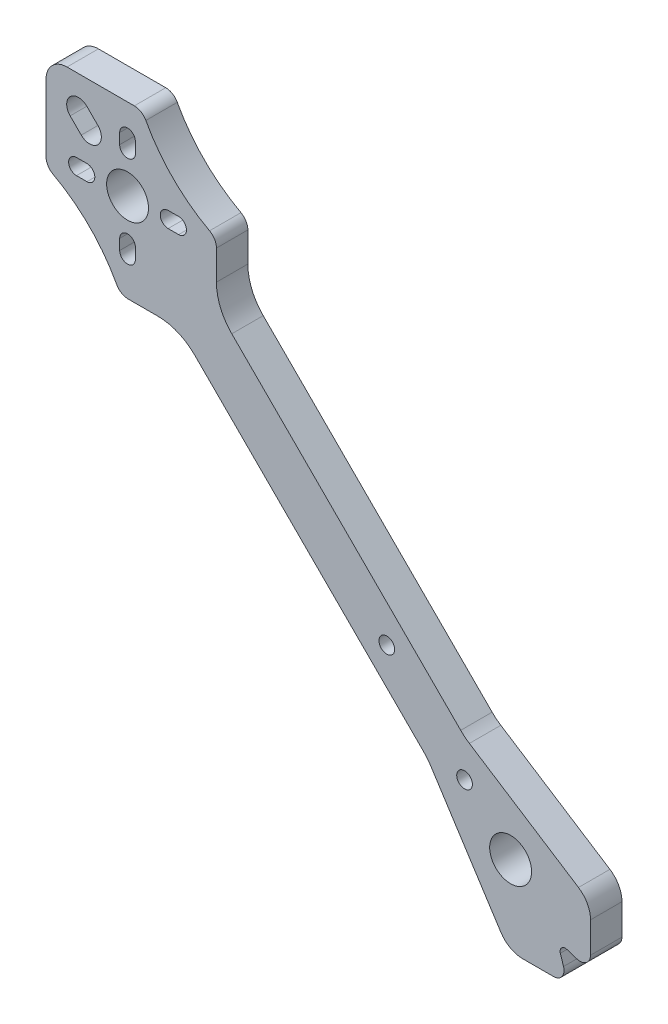
SolidWorks part; units mm, degrees
ref_plane "Alzado" through (0, 0, 0) normal (0, 0, 1) x (1, 0, 0)
ref_plane "Planta" through (0, 0, 0) normal (0, 1, 0) x (1, 0, 0)
ref_plane "Vista lateral" through (0, 0, 0) normal (1, 0, 0) x (0, 0, -1)
sketch "Croquis1" plane through (0, 0, 0) normal (0, 0, 1) x (1, 0, 0)
  line L0 (0, 0) -> (27.8544, 27.8544) construction
  line L1 (0, 0) -> (-42.4264, 42.4264) construction
  line L2 (0, 0) -> (0, 42.4264) construction
  line L3 (15.25, -15.25) -> (-15.25, -15.25) construction
  line L4 (15.25, -15.25) -> (15.25, 15.25) construction
  line L5 (15.25, 15.25) -> (-15.25, 15.25) construction
  line L6 (-15.25, -15.25) -> (-15.25, 15.25) construction
  line L7 (15.25, -15.25) -> (-15.25, 15.25) construction
  line L8 (15.25, 15.25) -> (-15.25, -15.25) construction
  line L9 (0, 42.4264) -> (-20, 42.4264) construction
  line L10 (-42.4264, 42.4264) -> (-38.8909, 45.9619) construction
  line L11 (-38.8909, 45.9619) -> (-31.0962, 38.1673) construction
  line L12 (-20, 42.7635) -> (-20, 80) construction
  line L13 (-42.4264, 42.4264) -> (-45.9619, 38.8909) construction
  line L14 (-45.9619, 38.8909) -> (-38.1673, 31.0962) construction
  line L15 (20, 42.7635) -> (20, 80) construction
  line L16 (38.8909, 45.9619) -> (31.0962, 38.1673) construction
  line L17 (42.4264, 42.4264) -> (38.8909, 45.9619) construction
  line L18 (42.4264, 42.4264) -> (45.9619, 38.8909) construction
  line L19 (-45.9619, -38.8909) -> (-38.1673, -31.0962) construction
  line L20 (0, 0) -> (-15.25, 0) construction
  line L21 (45.9619, 38.8909) -> (38.1673, 31.0962) construction
  line L22 (42.4264, -42.4264) -> (45.9619, -38.8909) construction
  line L23 (42.4264, -42.4264) -> (38.8909, -45.9619) construction
  line L24 (38.8909, -45.9619) -> (31.0962, -38.1673) construction
  line L25 (20, -42.7635) -> (20, -80) construction
  line L26 (-20, -42.7635) -> (-20, -80) construction
  line L27 (-38.8909, -45.9619) -> (-31.0962, -38.1673) construction
  line L28 (-42.4264, -42.4264) -> (-38.8909, -45.9619) construction
  line L29 (-42.4264, -42.4264) -> (-45.9619, -38.8909) construction
  line L30 (45.9619, -38.8909) -> (38.1673, -31.0962) construction
  line L31 (-20, 80) -> (20, 80) construction
  line L32 (0, 80) -> (0, 83) construction
  line L33 (-20, 80) -> (0, 83) construction
  line L34 (0, 83) -> (20, 80) construction
  line L35 (0, -80) -> (0, -83) construction
  line L36 (-20, -80) -> (20, -80) construction
  line L37 (0, -83) -> (20, -80) construction
  line L38 (-20, -80) -> (0, -83) construction
  line L39 (-11, -54) -> (-11, -67.5) construction
  line L41 (-15, -54) -> (-15, -67.5) construction
  line L43 (-13, -54) -> (-13, -67.5) construction
  line L44 (-9, -54) -> (-9, -67.5) construction
  line L45 (-7, -54) -> (-7, -67.5) construction
  line L46 (-5, -54) -> (-5, -67.5) construction
  line L47 (-3, -54) -> (-3, -67.5) construction
  line L48 (-1, -54) -> (-1, -67.5) construction
  line L49 (1, -54) -> (1, -67.5) construction
  line L50 (3, -54) -> (3, -67.5) construction
  line L51 (5, -54) -> (5, -67.5) construction
  line L52 (7, -54) -> (7, -67.5) construction
  line L53 (9, -54) -> (9, -67.5) construction
  line L54 (11, -54) -> (11, -67.5) construction
  line L55 (13, -54) -> (13, -67.5) construction
  line L56 (15, -54) -> (15, -67.5) construction
  line L57 (-11, -35) -> (-11, -48.5) construction
  line L58 (-9, -35) -> (-9, -48.5) construction
  line L59 (-7, -35) -> (-7, -48.5) construction
  line L60 (-5, -35) -> (-5, -48.5) construction
  line L61 (-3, -35) -> (-3, -48.5) construction
  line L62 (-1, -35) -> (-1, -48.5) construction
  line L63 (1, -35) -> (1, -48.5) construction
  line L64 (3, -35) -> (3, -48.5) construction
  line L65 (5, -35) -> (5, -48.5) construction
  line L66 (7, -35) -> (7, -48.5) construction
  line L67 (9, -35) -> (9, -48.5) construction
  line L68 (11, -35) -> (11, -48.5) construction
  line L69 (13, -35) -> (13, -48.5) construction
  line L70 (15, -35) -> (15, -48.5) construction
  line L71 (-15, -35) -> (-15, -48.5) construction
  line L72 (-13, -35) -> (-13, -48.5) construction
  line L73 (-15, 54) -> (-15, 67.5) construction
  line L74 (-13, 35) -> (-13, 48.5) construction
  line L75 (-15, 35) -> (-15, 48.5) construction
  line L76 (15, 35) -> (15, 48.5) construction
  line L77 (13, 35) -> (13, 48.5) construction
  line L78 (11, 35) -> (11, 48.5) construction
  line L79 (9, 35) -> (9, 48.5) construction
  line L80 (7, 35) -> (7, 48.5) construction
  line L81 (5, 35) -> (5, 48.5) construction
  line L82 (3, 35) -> (3, 48.5) construction
  line L83 (1, 35) -> (1, 48.5) construction
  line L84 (-1, 35) -> (-1, 48.5) construction
  line L85 (-3, 35) -> (-3, 48.5) construction
  line L86 (-5, 35) -> (-5, 48.5) construction
  line L87 (-7, 35) -> (-7, 48.5) construction
  line L88 (-9, 35) -> (-9, 48.5) construction
  line L89 (-11, 35) -> (-11, 48.5) construction
  line L90 (15, 54) -> (15, 67.5) construction
  line L91 (13, 54) -> (13, 67.5) construction
  line L92 (11, 54) -> (11, 67.5) construction
  line L93 (9, 54) -> (9, 67.5) construction
  line L94 (7, 54) -> (7, 67.5) construction
  line L95 (5, 54) -> (5, 67.5) construction
  line L96 (3, 54) -> (3, 67.5) construction
  line L97 (1, 54) -> (1, 67.5) construction
  line L98 (-1, 54) -> (-1, 67.5) construction
  line L99 (-3, 54) -> (-3, 67.5) construction
  line L100 (-5, 54) -> (-5, 67.5) construction
  line L101 (-7, 54) -> (-7, 67.5) construction
  line L102 (-9, 54) -> (-9, 67.5) construction
  line L103 (-13, 54) -> (-13, 67.5) construction
  line L104 (-11, 54) -> (-11, 67.5) construction
  line L105 (0, 0) -> (-8.4853, -8.4853) construction
  line L110 (-5.7118, -4.325) -> (-4.3076, -2.2188) construction
  line L111 (-4.325, -5.7118) -> (-2.2188, -4.3076) construction
  line L112 (-4.325, 5.7118) -> (-2.2188, 4.3076) construction
  line L113 (-5.7118, 4.325) -> (-4.3076, 2.2188) construction
  line L114 (5.7118, 4.325) -> (4.3076, 2.2188) construction
  line L115 (4.325, 5.7118) -> (2.2188, 4.3076) construction
  line L116 (4.325, -5.7118) -> (2.2188, -4.3076) construction
  line L117 (5.7118, -4.325) -> (4.3076, -2.2188) construction
  line L123 (-45.9619, 38.8909) -> (-31.0962, 24.0251) construction
  line L124 (-17.1122, 2.2943) -> (-30.516, 23.1236)
  line L125 (-31.8543, 24.7832) -> (-45.9619, 38.8909)
  line L126 (-45.9619, 38.8909) -> (-78.4889, 71.4178)
  line L127 (-31.0962, 24.0251) -> (-24.0251, 31.0962) construction
  line L128 (-38.8909, 45.9619) -> (-24.0251, 31.0962) construction
  line L129 (-2.2943, 17.1122) -> (-23.1236, 30.516)
  line L130 (-24.7832, 31.8543) -> (-38.8909, 45.9619)
  line L131 (-78.4889, 71.4178) -> (-71.4178, 78.4889)
  line L132 (0, 0) -> (-74.9533, 74.9533) construction
  line L135 (-74.9533, 74.9533) -> (-88.3883, 88.3883) construction
  line L168 (-38.8909, 45.9619) -> (-71.4178, 78.4889)
  line L171 (0, 0) -> (-6.364, 6.364) construction
  line L172 (-5.7629, 4.5039) -> (-5.1526, 2.6149)
  line L173 (-7.0557, 0) -> (-12.9076, 0)
  line L174 (-4.5039, 5.7629) -> (-2.6149, 5.1526)
  line L175 (0, 7.0557) -> (0, 12.9076)
  circle A0 centre (-15.25, 15.25) radius 4 construction
  circle A1 centre (-24.0416, 24.0416) radius 1.5 construction
  circle A2 centre (-38.8909, 38.8909) radius 1.5 construction
  arc A3 (-31.0962, 38.1673) -> (-20, 42.7635) centre (-26.5, 42.7635) ccw construction
  arc A4 (31.0962, 38.1673) -> (20, 42.7635) centre (26.5, 42.7635) cw construction
  circle A5 centre (38.8909, 38.8909) radius 1.5 construction
  circle A6 centre (24.0416, 24.0416) radius 1.5 construction
  circle A7 centre (15.25, 15.25) radius 4 construction
  circle A8 centre (15.25, -15.25) radius 4 construction
  circle A9 centre (24.0416, -24.0416) radius 1.5 construction
  circle A10 centre (38.8909, -38.8909) radius 1.5 construction
  arc A11 (31.0962, -38.1673) -> (20, -42.7635) centre (26.5, -42.7635) ccw construction
  circle A12 centre (-15.25, -15.25) radius 4 construction
  circle A13 centre (-24.0416, -24.0416) radius 1.5 construction
  circle A14 centre (-38.8909, -38.8909) radius 1.5 construction
  arc A15 (-31.0962, -38.1673) -> (-20, -42.7635) centre (-26.5, -42.7635) cw construction
  arc A16 (-38.1673, -31.0962) -> (-38.1673, 31.0962) centre (-69.2635, 0) ccw construction
  arc A17 (38.1673, -31.0962) -> (38.1673, 31.0962) centre (69.2635, 0) cw construction
  circle A18 centre (0, 0) radius 1.5 construction
  circle A19 centre (-16, -75) radius 1.5 construction
  circle A20 centre (-16, -30) radius 1.5 construction
  circle A21 centre (-16, 30) radius 1.5 construction
  circle A22 centre (-16, 75) radius 1.5 construction
  circle A23 centre (16, -75) radius 1.5 construction
  circle A24 centre (16, -30) radius 1.5 construction
  circle A25 centre (16, 30) radius 1.5 construction
  circle A26 centre (16, 75) radius 1.5 construction
  arc A27 (-15, -54) -> (-13, -54) centre (-14, -54) cw construction
  arc A28 (-15, -67.5) -> (-13, -67.5) centre (-14, -67.5) ccw construction
  arc A29 (-11, -54) -> (-9, -54) centre (-10, -54) cw construction
  arc A30 (-11, -67.5) -> (-9, -67.5) centre (-10, -67.5) ccw construction
  arc A31 (-7, -54) -> (-5, -54) centre (-6, -54) cw construction
  arc A32 (-7, -67.5) -> (-5, -67.5) centre (-6, -67.5) ccw construction
  arc A33 (-3, -54) -> (-1, -54) centre (-2, -54) cw construction
  arc A34 (-3, -67.5) -> (-1, -67.5) centre (-2, -67.5) ccw construction
  arc A35 (1, -54) -> (3, -54) centre (2, -54) cw construction
  arc A36 (1, -67.5) -> (3, -67.5) centre (2, -67.5) ccw construction
  arc A37 (5, -54) -> (7, -54) centre (6, -54) cw construction
  arc A38 (5, -67.5) -> (7, -67.5) centre (6, -67.5) ccw construction
  arc A39 (9, -54) -> (11, -54) centre (10, -54) cw construction
  arc A40 (9, -67.5) -> (11, -67.5) centre (10, -67.5) ccw construction
  arc A41 (13, -54) -> (15, -54) centre (14, -54) cw construction
  arc A42 (13, -67.5) -> (15, -67.5) centre (14, -67.5) ccw construction
  arc A43 (-11, -35) -> (-9, -35) centre (-10, -35) cw construction
  arc A44 (-11, -48.5) -> (-9, -48.5) centre (-10, -48.5) ccw construction
  arc A45 (-7, -35) -> (-5, -35) centre (-6, -35) cw construction
  arc A46 (-7, -48.5) -> (-5, -48.5) centre (-6, -48.5) ccw construction
  arc A47 (-3, -35) -> (-1, -35) centre (-2, -35) cw construction
  arc A48 (-3, -48.5) -> (-1, -48.5) centre (-2, -48.5) ccw construction
  arc A49 (1, -35) -> (3, -35) centre (2, -35) cw construction
  arc A50 (1, -48.5) -> (3, -48.5) centre (2, -48.5) ccw construction
  arc A51 (5, -35) -> (7, -35) centre (6, -35) cw construction
  arc A52 (5, -48.5) -> (7, -48.5) centre (6, -48.5) ccw construction
  arc A53 (9, -35) -> (11, -35) centre (10, -35) cw construction
  arc A54 (9, -48.5) -> (11, -48.5) centre (10, -48.5) ccw construction
  arc A55 (13, -35) -> (15, -35) centre (14, -35) cw construction
  arc A56 (13, -48.5) -> (15, -48.5) centre (14, -48.5) ccw construction
  arc A57 (-15, -35) -> (-13, -35) centre (-14, -35) cw construction
  arc A58 (-15, -48.5) -> (-13, -48.5) centre (-14, -48.5) ccw construction
  arc A59 (-15, 48.5) -> (-13, 48.5) centre (-14, 48.5) cw construction
  arc A60 (-15, 35) -> (-13, 35) centre (-14, 35) ccw construction
  arc A61 (13, 48.5) -> (15, 48.5) centre (14, 48.5) cw construction
  arc A62 (13, 35) -> (15, 35) centre (14, 35) ccw construction
  arc A63 (9, 48.5) -> (11, 48.5) centre (10, 48.5) cw construction
  arc A64 (9, 35) -> (11, 35) centre (10, 35) ccw construction
  arc A65 (5, 48.5) -> (7, 48.5) centre (6, 48.5) cw construction
  arc A66 (5, 35) -> (7, 35) centre (6, 35) ccw construction
  arc A67 (1, 48.5) -> (3, 48.5) centre (2, 48.5) cw construction
  arc A68 (1, 35) -> (3, 35) centre (2, 35) ccw construction
  arc A69 (-3, 48.5) -> (-1, 48.5) centre (-2, 48.5) cw construction
  arc A70 (-3, 35) -> (-1, 35) centre (-2, 35) ccw construction
  arc A71 (-7, 48.5) -> (-5, 48.5) centre (-6, 48.5) cw construction
  arc A72 (-7, 35) -> (-5, 35) centre (-6, 35) ccw construction
  arc A73 (-11, 48.5) -> (-9, 48.5) centre (-10, 48.5) cw construction
  arc A74 (-11, 35) -> (-9, 35) centre (-10, 35) ccw construction
  arc A75 (13, 67.5) -> (15, 67.5) centre (14, 67.5) cw construction
  arc A76 (13, 54) -> (15, 54) centre (14, 54) ccw construction
  arc A77 (9, 67.5) -> (11, 67.5) centre (10, 67.5) cw construction
  arc A78 (9, 54) -> (11, 54) centre (10, 54) ccw construction
  arc A79 (5, 67.5) -> (7, 67.5) centre (6, 67.5) cw construction
  arc A80 (5, 54) -> (7, 54) centre (6, 54) ccw construction
  arc A81 (1, 67.5) -> (3, 67.5) centre (2, 67.5) cw construction
  arc A82 (1, 54) -> (3, 54) centre (2, 54) ccw construction
  arc A83 (-3, 67.5) -> (-1, 67.5) centre (-2, 67.5) cw construction
  arc A84 (-3, 54) -> (-1, 54) centre (-2, 54) ccw construction
  arc A85 (-7, 67.5) -> (-5, 67.5) centre (-6, 67.5) cw construction
  arc A86 (-7, 54) -> (-5, 54) centre (-6, 54) ccw construction
  arc A87 (-11, 67.5) -> (-9, 67.5) centre (-10, 67.5) cw construction
  arc A88 (-11, 54) -> (-9, 54) centre (-10, 54) ccw construction
  arc A89 (-15, 67.5) -> (-13, 67.5) centre (-14, 67.5) cw construction
  arc A90 (-15, 54) -> (-13, 54) centre (-14, 54) ccw construction
  arc A91 (-4.325, -5.7118) -> (-5.7118, -4.325) centre (-4.8797, -4.8797) cw construction
  arc A92 (-5.7118, 4.325) -> (-4.325, 5.7118) centre (-4.8797, 4.8797) cw construction
  arc A93 (4.325, 5.7118) -> (5.7118, 4.325) centre (4.8797, 4.8797) cw construction
  arc A94 (5.7118, -4.325) -> (4.325, -5.7118) centre (4.8797, -4.8797) cw construction
  circle A95 centre (0, 0) radius 1.5 construction
  arc A96 (2.2188, -4.3076) -> (-2.2188, -4.3076) centre (0, -7.6358) ccw construction
  arc A97 (4.3076, 2.2188) -> (4.3076, -2.2188) centre (7.6358, 0) ccw construction
  arc A98 (-2.2188, 4.3076) -> (2.2188, 4.3076) centre (0, 7.6358) ccw construction
  arc A99 (-4.3076, 2.2188) -> (-4.3076, -2.2188) centre (-7.6358, 0) cw construction
  circle A102 centre (-38.8909, 38.8909) radius 1.5
  circle A103 centre (-24.0416, 24.0416) radius 1.5
  circle A104 centre (-15.25, 15.25) radius 4
  arc A112 (0, 12.9076) -> (-2.2943, 17.1122) centre (-5, 12.9076) ccw
  arc A113 (-12.9076, 0) -> (-17.1122, 2.2943) centre (-12.9076, 5) cw
  arc A114 (-23.1236, 30.516) -> (-24.7832, 31.8543) centre (-17.7121, 38.9253) cw
  arc A115 (-31.8543, 24.7832) -> (-30.516, 23.1236) centre (-38.9253, 17.7121) cw
  arc A143 (-4.5039, 5.7629) -> (-5.7629, 4.5039) centre (-4.8114, 4.8114) ccw
  arc A144 (-2.6149, 5.1526) -> (0, 7.0557) centre (-2, 7.0557) ccw
  arc A145 (-5.1526, 2.6149) -> (-7.0557, 0) centre (-7.0557, 2) cw
  circle A146 centre (-88.3883, 88.3883) radius 65 construction
  point P35 (-34.9935, 42.0646)
  point P37 (44.1942, 40.6586)
  point P45 (44.1942, -40.6586)
  point P61 (-34.9935, -42.0646)
  point P305 (0, 0)
  point P308 (-2.8284, 0)
  point P327 (0, 4.3076)
  point P330 (-4.3076, 0)
  point P338 (0, 15.6358)
  point P341 (-15.6358, 0)
  dimension "D2" = 8
  dimension "D4" = 5
  dimension "D8" = 6.5
  dimension "D10" = 3
  dimension "D11" = 3
  dimension "D13" = 4
  dimension "D15" = 3
  dimension "D16" = 3
  dimension "D18" = 45
  dimension "D26" = 1
  dimension "D28" = 4
  dimension "D29" = 19
  dimension "D31" = 130
  dimension "D32" = 9
  dimension "D33" = 5
  dimension "D34" = 10
  dimension "D39" = 1
  dimension "D40" = 2
  dimension "D30" = 5
  dimension "D1" = 30.5
  dimension "D3" = 60
  dimension "D5" = 21
  dimension "D6" = 20
  dimension "D7" = 5
  dimension "D9" = 5
  dimension "D12" = 80
  dimension "D14" = 5
  dimension "D17" = 4
  dimension "D19" = 2
  dimension "D20" = 13.5
  dimension "D21" = 7.5
  dimension "D22" = 5
  dimension "D25" = 12
  dimension "D35" = 125
  dimension "D23" = 8
  dimension "D24" = 2
  dimension "D27" = 4
extrude "Saliente-Extruir1" add sketch "Croquis1" along normal blind 6
sketch "Croquis4" plane through (0, 0, 6) normal (0, 0, 1) x (1, 0, 0)
  line L0 (-78.4889, 71.4178) -> (-89.8026, 71.4178)
  line L1 (-89.8026, 71.4178) -> (-103.9447, 85.5599)
  line L2 (-88.3883, 88.3883) -> (-103.9447, 103.9447) construction
  line L3 (-103.9447, 85.5599) -> (-103.9447, 103.9447)
  line L4 (-71.4178, 78.4889) -> (-71.4178, 89.8026)
  line L5 (-71.4178, 89.8026) -> (-85.5599, 103.9447)
  line L6 (-85.5599, 103.9447) -> (-103.9447, 103.9447)
  line L7 (-78.4889, 71.4178) -> (-71.4178, 78.4889)
  circle A0 centre (-88.3883, 88.3883) radius 4
  dimension "D1" = 22
  dimension "D2" = 13
extrude "Saliente-Extruir3" add sketch "Croquis4" against normal up to vertex (6 mm away)
sketch "Croquis5" plane through (0, 0, 6) normal (0, 0, 1) x (1, 0, 0)
  line L0 (-88.3883, 88.3883) -> (-103.9447, 103.9447) construction
  line L2 (-99.3485, 96.1665) -> (-97.2272, 94.0452)
  line L4 (-94.0452, 97.2272) -> (-96.1665, 99.3485)
  line L6 (-91.2168, 91.2168) -> (-94.0452, 94.0452) construction
  line L7 (-88.3883, 88.3883) -> (-82.0244, 88.3883) construction
  line L8 (-89.8883, 80.6383) -> (-89.8883, 78.6383)
  line L9 (-80.6383, 86.8883) -> (-78.6383, 86.8883)
  line L11 (-80.6383, 89.8883) -> (-78.6383, 89.8883)
  line L13 (-86.8883, 80.6383) -> (-86.8883, 78.6383)
  line L14 (-96.1383, 89.8883) -> (-98.1383, 89.8883)
  line L15 (-96.1383, 86.8883) -> (-98.1383, 86.8883)
  line L16 (-86.8883, 96.1383) -> (-86.8883, 98.1383)
  line L17 (-89.8883, 96.1383) -> (-89.8883, 98.1383)
  arc A0 (-99.3485, 96.1665) -> (-96.1665, 99.3485) centre (-97.7575, 97.7575) cw
  arc A1 (-97.2272, 94.0452) -> (-94.0452, 97.2272) centre (-95.6362, 95.6362) ccw
  circle A2 centre (-88.3883, 88.3883) radius 4 construction
  arc A3 (-78.6383, 89.8883) -> (-78.6383, 86.8883) centre (-78.6383, 88.3883) cw
  arc A4 (-80.6383, 86.8883) -> (-80.6383, 89.8883) centre (-80.6383, 88.3883) cw
  arc A5 (-86.8883, 78.6383) -> (-89.8883, 78.6383) centre (-88.3883, 78.6383) cw
  arc A6 (-89.8883, 80.6383) -> (-86.8883, 80.6383) centre (-88.3883, 80.6383) cw
  arc A7 (-98.1383, 86.8883) -> (-98.1383, 89.8883) centre (-98.1383, 88.3883) cw
  arc A8 (-96.1383, 89.8883) -> (-96.1383, 86.8883) centre (-96.1383, 88.3883) cw
  arc A9 (-89.8883, 98.1383) -> (-86.8883, 98.1383) centre (-88.3883, 98.1383) cw
  arc A10 (-86.8883, 96.1383) -> (-89.8883, 96.1383) centre (-88.3883, 96.1383) cw
  point P23 (-82.1383, 88.3883)
  point P43 (-88.3883, 88.3883)
  dimension "D1" = 3
  dimension "D2" = 4
  dimension "D3" = 4.5
  dimension "D4" = 2.25
  dimension "D5" = 3
  dimension "D6" = 1.5
  dimension "D7" = 2
  dimension "D8" = 6.25
extrude "Cortar-Extruir1" cut sketch "Croquis5" against normal up to vertex (6 mm away)
fillet "Redondeo3" radius 4 1 edges at (-103.9447, 103.9447, 3)
sketch "Croquis7" plane through (0, 0, 6) normal (0, 0, 1) x (1, 0, 0)
  line L0 (-103.9447, 85.5599) -> (-89.8026, 71.4178)
  line L3 (-88.3883, 88.3883) -> (-82.0244, 82.0244) construction
  line L4 (-85.5599, 103.9447) -> (-71.4178, 89.8026)
  arc A0 (-103.9447, 85.5599) -> (-89.8026, 71.4178) centre (-116.8736, 58.4889) cw
  arc A1 (-85.5599, 103.9447) -> (-71.4178, 89.8026) centre (-58.4889, 116.8736) ccw
  dimension "D1" = 30
extrude "Cortar-Extruir2" cut sketch "Croquis7" against normal up to vertex (6 mm away)
fillet "Redondeo4" radius 2.5 4 edges at (-85.5599, 103.9447, 3) (-71.4178, 89.8026, 3) (-89.8026, 71.4178, 3) (-103.9447, 85.5599, 3)
fillet "Redondeo6" radius 10 2 edges at (-71.4178, 78.4889, 3) (-78.4889, 71.4178, 3)
sketch "Croquis8" plane through (0, 0, 6) normal (0, 0, 1) x (1, 0, 0)
  line L0 (-99.9447, 103.9447) -> (-87.093, 103.9447)
  line L1 (-103.9447, 99.9447) -> (-103.9447, 87.093)
  line L2 (-96.1665, 99.3485) -> (-94.0452, 97.2272)
  line L3 (-99.3485, 96.1665) -> (-97.2272, 94.0452)
  line L4 (-86.8883, 98.1383) -> (-86.8883, 96.1383)
  line L5 (-89.8883, 98.1383) -> (-89.8883, 96.1383)
  line L6 (-78.6383, 89.8883) -> (-80.6383, 89.8883)
  line L7 (-78.6383, 86.8883) -> (-80.6383, 86.8883)
  line L8 (-86.8883, 78.6383) -> (-86.8883, 80.6383)
  line L9 (-89.8883, 78.6383) -> (-89.8883, 80.6383)
  line L10 (-98.1383, 86.8883) -> (-96.1383, 86.8883)
  line L11 (-98.1383, 89.8883) -> (-96.1383, 89.8883)
  arc A0 (-84.8927, 102.6315) -> (-72.7309, 90.4698) centre (-58.4889, 116.8736) ccw
  arc A1 (-84.8927, 102.6315) -> (-87.093, 103.9447) centre (-87.093, 101.4447) ccw
  arc A2 (-99.9447, 103.9447) -> (-103.9447, 99.9447) centre (-99.9447, 99.9447) ccw
  arc A3 (-103.9447, 87.093) -> (-102.6315, 84.8927) centre (-101.4447, 87.093) ccw
  arc A4 (-102.6315, 84.8927) -> (-90.4698, 72.7309) centre (-116.8736, 58.4889) cw
  arc A5 (-90.4698, 72.7309) -> (-88.2695, 71.4178) centre (-88.2695, 73.9178) ccw
  arc A6 (-96.1665, 99.3485) -> (-99.3485, 96.1665) centre (-97.7575, 97.7575) ccw
  arc A7 (-94.0452, 97.2272) -> (-97.2272, 94.0452) centre (-95.6362, 95.6362) cw
  circle A8 centre (-88.3883, 88.3883) radius 4
  arc A9 (-89.8883, 98.1383) -> (-86.8883, 98.1383) centre (-88.3883, 98.1383) cw
  arc A10 (-89.8883, 96.1383) -> (-86.8883, 96.1383) centre (-88.3883, 96.1383) ccw
  arc A11 (-80.6383, 89.8883) -> (-80.6383, 86.8883) centre (-80.6383, 88.3883) ccw
  arc A12 (-78.6383, 89.8883) -> (-78.6383, 86.8883) centre (-78.6383, 88.3883) cw
  arc A13 (-86.8883, 80.6383) -> (-89.8883, 80.6383) centre (-88.3883, 80.6383) ccw
  arc A14 (-86.8883, 78.6383) -> (-89.8883, 78.6383) centre (-88.3883, 78.6383) cw
  arc A15 (-96.1383, 86.8883) -> (-96.1383, 89.8883) centre (-96.1383, 88.3883) ccw
  arc A16 (-98.1383, 86.8883) -> (-98.1383, 89.8883) centre (-98.1383, 88.3883) cw
  point P67 (-88.3883, 88.3883)
  dimension "D1" = 4
